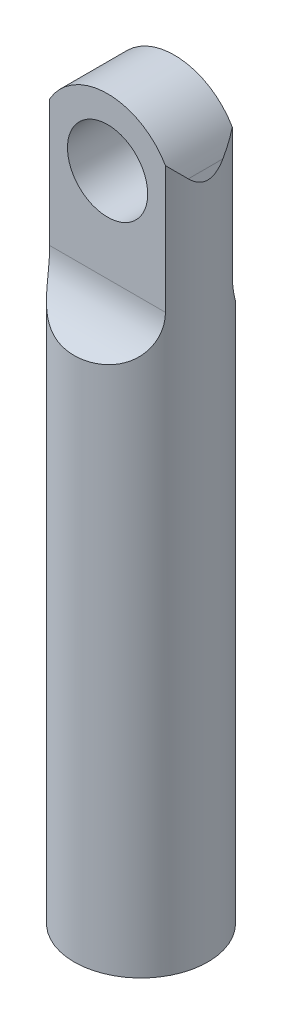
SolidWorks part; units mm, degrees
ref_plane "Front Plane" through (0, 0, 0) normal (0, 0, 1) x (1, 0, 0)
ref_plane "Top Plane" through (0, 0, 0) normal (0, 1, 0) x (1, 0, 0)
ref_plane "Right Plane" through (0, 0, 0) normal (1, 0, 0) x (0, 0, -1)
sketch "Sketch1" plane through (0, 0, 0) normal (0, 1, 0) x (1, 0, 0)
  circle A0 centre (0, 0) radius 5
  dimension "D1" = 10
extrude "Boss-Extrude1" add sketch "Sketch1" along normal blind 55
sketch "Sketch5" plane through (0, 0, 0) normal (1, 0, 0) x (0, 0, -1)
  line L0 (-2.5, 55) -> (-2.5, 43)
  line L1 (5, 55) -> (-5, 55) construction
  line L2 (-2.5, 55) -> (-6.5, 55)
  line L3 (-6.5, 55) -> (-6.5, 39)
  line L4 (-5, 55) -> (-5, 0) construction
  line L5 (0, 65) -> (0, 49.2798) construction
  line L6 (6.5, 55) -> (6.5, 39)
  line L7 (2.5, 55) -> (6.5, 55)
  line L8 (2.5, 55) -> (2.5, 43)
  arc A0 (-6.5, 39) -> (-2.5, 43) centre (-6.5, 43) ccw
  arc A1 (6.5, 39) -> (2.5, 43) centre (6.5, 43) cw
  dimension "D1" = 2.5
  dimension "D2" = 8
  dimension "D3" = 12
extrude "Cut-Extrude2" cut sketch "Sketch5" against normal through all both and the other way through all
sketch "Sketch6" plane through (0, 0, 2.5) normal (0, 0, 1) x (1, 0, 0)
  line L0 (4.3301, 55) -> (-4.3301, 55) construction
  circle A0 centre (0, 50) radius 3
  dimension "D1" = 6
  dimension "D2" = 5
extrude "Cut-Extrude3" cut sketch "Sketch6" against normal through all
sketch "Sketch7" plane through (0, 0, -2.5) normal (0, 0, -1) x (-1, 0, 0)
  line L0 (-4.8296, 51.2941) -> (-10.893, 28.6653)
  line L1 (-10.893, 28.6653) -> (-10.893, 70.0834)
  line L2 (-10.893, 70.0834) -> (10.893, 70.0834)
  line L3 (10.893, 70.0834) -> (10.893, 28.6653)
  line L4 (10.893, 28.6653) -> (4.8296, 51.2941)
  line L6 (0, 50) -> (0, 70.0834) construction
  line L7 (4.3301, 55) -> (-4.3301, 55) construction
  arc A0 (4.8296, 51.2941) -> (-4.8296, 51.2941) centre (0, 50) ccw
  dimension "D1" = 30
extrude "Cut-Extrude4" cut sketch "Sketch7" against normal through all
sketch "Sketch8" plane through (0, 0, 0) normal (0, -1, 0) x (1, 0, 0)
  line L0 (-1.5, 2) -> (-1.5, -2)
  line L1 (1.5, 2) -> (1.5, -2)
  arc A0 (-1.5, -2) -> (1.5, -2) centre (0, 0) ccw
  arc A1 (1.5, 2) -> (-1.5, 2) centre (0, 0) ccw
  dimension "D1" = 5
  dimension "D2" = 3
  dimension "D3" = 1.5
extrude "Cut-Extrude5" cut sketch "Sketch8" against normal blind 6
sketch "Sketch9" plane through (0, 0, 0) normal (0, -1, 0) x (1, 0, 0)
  circle A0 centre (0, 0) radius 5 construction
  circle A1 centre (0, 0) radius 5
  circle A2 centre (0, 0) radius 7.5
  dimension "D1" = 15
